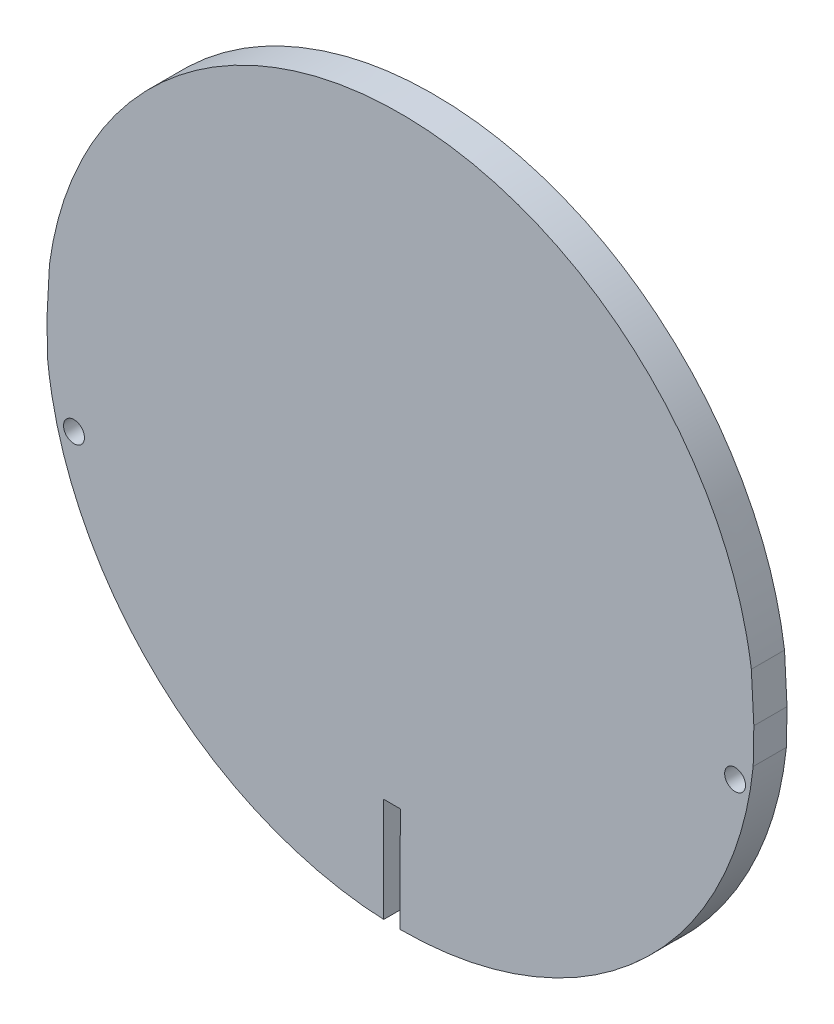
SolidWorks part; units mm, degrees
ref_plane "Front Plane" through (0, 0, 0) normal (0, 0, 1) x (1, 0, 0)
ref_plane "Top Plane" through (0, 0, 0) normal (0, 1, 0) x (1, 0, 0)
ref_plane "Right Plane" through (0, 0, 0) normal (1, 0, 0) x (0, 0, -1)
sketch "Sketch1" plane through (0, 0, 377.2094) normal (0, 0, 1) x (1, 0, 0)
  line L8 (-33.7995, -0.0171) -> (-33.7401, -3.4188)
  line L9 (33.7402, -3.4188) -> (33.7996, -0.0171)
  line L10 (33.7996, -0.0171) -> (33.5604, 4.5461)
  line L11 (-33.5604, 4.5461) -> (-33.7995, -0.0171)
  line L12 (-33.7995, -0.0171) -> (-33.7401, -3.4188)
  line L13 (33.7402, -3.4188) -> (33.7996, -0.0171)
  line L14 (33.7996, -0.0171) -> (33.5604, 4.5461)
  line L15 (-33.5604, 4.5461) -> (-33.7995, -0.0171)
  spline S4 degree 3 poles (3584.2823, 1682.1592) (1891.8794, 981.7265) (-94.167, 198.9267) (-32.2457, -10.4865) (-31.7386, -11.9486) (-31.1278, -13.3816) (-30.6974, -14.3304) (-30.4704, -14.8019) (-29.2902, -17.1196) (-27.6449, -19.7403) (-25.6469, -22.1139) (-24.5884, -23.2589) (-24.2247, -23.6345) (-23.482, -24.3673) (-21.5901, -26.1504) (-18.7057, -28.3179) (-15.9808, -29.8236) (-14.107, -30.7477) (-13.1527, -31.1642) (-10.2562, -32.2793) (-7.778, -32.9883) (-5.2143, -33.4059) (-4.182, -33.5493) (-3.6613, -33.6093) (-2.1045, -33.752) (-1.0692, -33.7985) (2.0296, -33.8017) (4.086, -33.6221) (7.1551, -33.0587) (8.1781, -32.8207) (10.177, -32.2566) (11.1581, -31.9299) (14.0494, -30.8232) (15.9079, -29.9178) (18.1367, -28.5564) (18.5769, -28.2731) (19.4387, -27.6895) (20.707, -26.7866) (21.9036, -25.8034) (23.4386, -24.4244) (24.5444, -23.3394) (25.5786, -22.174) (26.2518, -21.3787) (26.581, -20.9708) (28.1709, -18.9029) (29.2697, -17.1529) (30.6789, -14.3959) (31.1088, -13.4548) (31.8841, -11.5261) (32.23, -10.5349) (99.7864, 216.9461) (-2290.3338, 992.2204) (3927.4834, -154.8641) knots -6.532325 -6.532325 -6.532325 -6.532325 0.0625 0.0625 0.09375 0.109375 0.109375 0.125 0.125 0.1875 0.21875 0.21875 0.234375 0.234375 0.25 0.3125 0.34375 0.34375 0.375 0.375 0.4375 0.453125 0.453125 0.46875 0.46875 0.5 0.5 0.5625 0.5625 0.59375 0.59375 0.625 0.625 0.6875 0.6875 0.703125 0.703125 0.71875 0.75 0.75 0.78125 0.796875 0.796875 0.8125 0.8125 0.875 0.875 0.90625 0.90625 0.9375 0.9375 8.025461 8.025461 8.025461 8.025461 only from (-33.7401, -3.4188) to (33.7402, -3.4188)
  spline S5 degree 3 poles (-3548.6792, -1753.5382) (-1588.5004, -923.6815) (94.7973, -181.1863) (31.8946, 11.4023) (31.3611, 12.8157) (30.7295, 14.1982) (30.2866, 15.113) (30.0537, 15.5679) (28.8457, 17.8053) (27.7362, 19.4878) (25.8529, 21.8475) (25.1886, 22.6067) (23.7865, 24.0699) (23.0451, 24.7766) (20.7523, 26.7783) (18.3111, 28.5582) (15.6406, 29.9959) (14.2667, 30.657) (13.8011, 30.8682) (12.8648, 31.268) (12.3937, 31.4568) (10.0246, 32.3475) (7.1153, 33.1595) (4.1023, 33.5707) (2.0702, 33.754) (1.0537, 33.7991) (-1.9787, 33.8028) (-4.4872, 33.5877) (-6.9715, 33.0844) (-7.9632, 32.8597) (-8.4594, 32.7353) (-9.9337, 32.3298) (-10.8974, 32.0168) (-13.7346, 30.9575) (-15.5548, 30.0922) (-17.7347, 28.7982) (-18.1659, 28.5288) (-19.0186, 27.9683) (-19.4392, 27.6779) (-20.674, 26.7832) (-21.4652, 26.1531) (-23.7487, 24.1676) (-25.1511, 22.7176) (-26.7425, 20.7348) (-27.0534, 20.3287) (-27.655, 19.5045) (-28.5257, 18.252) (-29.3043, 16.9523) (-30.7455, 14.2933) (-31.5513, 12.4411) (-32.5069, 9.533) (-32.7811, 8.5477) (-77.2289, -184.7715) (1567.6211, -755.0924) (-3962.2208, 280.2012) knots -6.201583 -6.201583 -6.201583 -6.201583 0.0625 0.0625 0.09375 0.109375 0.109375 0.125 0.125 0.1875 0.1875 0.21875 0.21875 0.25 0.25 0.3125 0.34375 0.34375 0.359375 0.359375 0.375 0.375 0.4375 0.46875 0.46875 0.5 0.5 0.5625 0.578125 0.578125 0.59375 0.59375 0.625 0.625 0.6875 0.6875 0.703125 0.703125 0.71875 0.71875 0.75 0.75 0.8125 0.8125 0.828125 0.828125 0.84375 0.875 0.875 0.9375 0.9375 0.96875 0.96875 7.021867 7.021867 7.021867 7.021867 only from (33.5604, 4.5461) to (-33.5604, 4.5461)
  spline S6 degree 3 poles (-33.7401, -3.4188) (-33.5219, -5.4967) (-33.1218, -7.5236) (-32.2457, -10.4865) (-31.7386, -11.9486) (-31.1278, -13.3816) (-30.6974, -14.3304) (-30.4704, -14.8019) (-29.2902, -17.1196) (-27.6449, -19.7403) (-25.6469, -22.1139) (-24.5884, -23.2589) (-24.2247, -23.6345) (-23.482, -24.3673) (-21.5901, -26.1504) (-18.7057, -28.3179) (-15.9808, -29.8236) (-14.107, -30.7477) (-13.1527, -31.1642) (-10.2562, -32.2793) (-7.778, -32.9883) (-5.2143, -33.4059) (-4.182, -33.5493) (-3.6613, -33.6093) (-2.1045, -33.752) (-1.0692, -33.7985) (2.0296, -33.8017) (4.086, -33.6221) (7.1551, -33.0587) (8.1781, -32.8207) (10.177, -32.2566) (11.1581, -31.9299) (14.0494, -30.8232) (15.9079, -29.9178) (18.1367, -28.5564) (18.5769, -28.2731) (19.4387, -27.6895) (20.707, -26.7866) (21.9036, -25.8034) (23.4386, -24.4244) (24.5444, -23.3394) (25.5786, -22.174) (26.2518, -21.3787) (26.581, -20.9708) (28.1709, -18.9029) (29.2697, -17.1529) (30.6789, -14.3959) (31.1088, -13.4548) (31.8841, -11.5261) (32.23, -10.5349) (33.1196, -7.5393) (33.5217, -5.4996) (33.7402, -3.4188) knots 0 0 0 0 0.0625 0.0625 0.09375 0.109375 0.109375 0.125 0.125 0.1875 0.21875 0.21875 0.234375 0.234375 0.25 0.3125 0.34375 0.34375 0.375 0.375 0.4375 0.453125 0.453125 0.46875 0.46875 0.5 0.5 0.5625 0.5625 0.59375 0.59375 0.625 0.625 0.6875 0.6875 0.703125 0.703125 0.71875 0.75 0.75 0.78125 0.796875 0.796875 0.8125 0.8125 0.875 0.875 0.90625 0.90625 0.9375 0.9375 1 1 1 1
  spline S7 degree 3 poles (33.5604, 4.5461) (33.2821, 6.5674) (32.8314, 8.5342) (31.8946, 11.4023) (31.3611, 12.8157) (30.7295, 14.1982) (30.2866, 15.113) (30.0537, 15.5679) (28.8457, 17.8053) (27.7362, 19.4878) (25.8529, 21.8475) (25.1886, 22.6067) (23.7865, 24.0699) (23.0451, 24.7766) (20.7523, 26.7783) (18.3111, 28.5582) (15.6406, 29.9959) (14.2667, 30.657) (13.8011, 30.8682) (12.8648, 31.268) (12.3937, 31.4568) (10.0246, 32.3475) (7.1153, 33.1595) (4.1023, 33.5707) (2.0702, 33.754) (1.0537, 33.7991) (-1.9787, 33.8028) (-4.4872, 33.5877) (-6.9715, 33.0844) (-7.9632, 32.8597) (-8.4594, 32.7353) (-9.9337, 32.3298) (-10.8974, 32.0168) (-13.7346, 30.9575) (-15.5548, 30.0922) (-17.7347, 28.7982) (-18.1659, 28.5288) (-19.0186, 27.9683) (-19.4392, 27.6779) (-20.674, 26.7832) (-21.4652, 26.1531) (-23.7487, 24.1676) (-25.1511, 22.7176) (-26.7425, 20.7348) (-27.0534, 20.3287) (-27.655, 19.5045) (-28.5257, 18.252) (-29.3043, 16.9523) (-30.7455, 14.2933) (-31.5513, 12.4411) (-32.5069, 9.533) (-32.7811, 8.5477) (-33.2376, 6.5619) (-33.4209, 5.5589) (-33.5604, 4.5461) knots 0 0 0 0 0.0625 0.0625 0.09375 0.109375 0.109375 0.125 0.125 0.1875 0.1875 0.21875 0.21875 0.25 0.25 0.3125 0.34375 0.34375 0.359375 0.359375 0.375 0.375 0.4375 0.46875 0.46875 0.5 0.5 0.5625 0.578125 0.578125 0.59375 0.59375 0.625 0.625 0.6875 0.6875 0.703125 0.703125 0.71875 0.71875 0.75 0.75 0.8125 0.8125 0.828125 0.828125 0.84375 0.875 0.875 0.9375 0.9375 0.96875 0.96875 1 1 1 1
  dimension "D1" = 1
extrude "Boss-Extrude1" add sketch "Sketch1" against normal blind 3.175
sketch "Sketch2" plane through (0, 0, 377.2094) normal (0, 0, 1) x (1, 0, 0)
  circle A0 centre (32.0093, -5.359) radius 1 construction
  circle A1 centre (-31.2161, -8.1644) radius 1 construction
  circle A2 centre (32.0093, -5.359) radius 1
  circle A3 centre (-31.2161, -8.1644) radius 1
extrude "Cut-Extrude1" cut sketch "Sketch2" against normal blind 3.175
sketch "Sketch3" plane through (0, 0, 377.2094) normal (0, 0, 1) x (1, 0, 0)
  line L0 (0, 0) -> (-0.0186, -33.7996) construction
  line L1 (-1.6006, -23.7996) -> (1.5744, -23.7996)
  line L13 (-1.6006, -23.7996) -> (-1.6006, -34.7702)
  line L14 (-1.6006, -34.7702) -> (1.5744, -34.7702)
  line L15 (1.5744, -34.7702) -> (1.5744, -23.7996)
  line L16 (-23.7238, -25.4681) -> (-15.8908, -17.7871)
  line L17 (-18.1137, -15.5202) -> (-15.8908, -17.7871)
  line L18 (-18.1137, -15.5202) -> (-25.9468, -23.2011)
  line L19 (-25.9468, -23.2011) -> (-23.7238, -25.4681)
  line L20 (25.6995, -23.473) -> (17.9421, -15.7156)
  line L21 (15.697, -17.9607) -> (17.9421, -15.7156)
  line L22 (15.697, -17.9607) -> (23.4544, -25.718)
  line L23 (23.4544, -25.718) -> (25.6995, -23.473)
  spline S0 degree 3 poles (-33.7401, -3.4188) (-33.5219, -5.4967) (-33.1218, -7.5236) (-32.2457, -10.4865) (-31.7386, -11.9486) (-31.1278, -13.3816) (-30.6974, -14.3304) (-30.4704, -14.8019) (-29.2902, -17.1196) (-27.6449, -19.7403) (-25.6469, -22.1139) (-24.5884, -23.2589) (-24.2247, -23.6345) (-23.482, -24.3673) (-21.5901, -26.1504) (-18.7057, -28.3179) (-15.9808, -29.8236) (-14.107, -30.7477) (-13.1527, -31.1642) (-10.2562, -32.2793) (-7.778, -32.9883) (-5.2143, -33.4059) (-4.182, -33.5493) (-3.6613, -33.6093) (-2.1045, -33.752) (-1.0692, -33.7985) (2.0296, -33.8017) (4.086, -33.6221) (7.1551, -33.0587) (8.1781, -32.8207) (10.177, -32.2566) (11.1581, -31.9299) (14.0494, -30.8232) (15.9079, -29.9178) (18.1367, -28.5564) (18.5769, -28.2731) (19.4387, -27.6895) (20.707, -26.7866) (21.9036, -25.8034) (23.4386, -24.4244) (24.5444, -23.3394) (25.5786, -22.174) (26.2518, -21.3787) (26.581, -20.9708) (28.1709, -18.9029) (29.2697, -17.1529) (30.6789, -14.3959) (31.1088, -13.4548) (31.8841, -11.5261) (32.23, -10.5349) (33.1196, -7.5393) (33.5217, -5.4996) (33.7402, -3.4188) knots 0 0 0 0 0.0625 0.0625 0.09375 0.109375 0.109375 0.125 0.125 0.1875 0.21875 0.21875 0.234375 0.234375 0.25 0.3125 0.34375 0.34375 0.375 0.375 0.4375 0.453125 0.453125 0.46875 0.46875 0.5 0.5 0.5625 0.5625 0.59375 0.59375 0.625 0.625 0.6875 0.6875 0.703125 0.703125 0.71875 0.75 0.75 0.78125 0.796875 0.796875 0.8125 0.8125 0.875 0.875 0.90625 0.90625 0.9375 0.9375 1 1 1 1 construction
  spline S1 degree 3 poles (-29.7439, -3.1693) (-29.5425, -4.9938) (-29.1806, -6.7723) (-28.3985, -9.3718) (-27.9469, -10.6542) (-27.4049, -11.9108) (-27.0234, -12.7428) (-26.8223, -13.1562) (-25.777, -15.1877) (-24.8075, -16.7189) (-23.1487, -18.8713) (-22.5611, -19.5643) (-21.3169, -20.9015) (-20.6591, -21.5463) (-18.624, -23.3704) (-17.1738, -24.4556) (-14.8518, -25.8775) (-14.053, -26.3166) (-12.4057, -27.1253) (-11.5665, -27.4902) (-9.0202, -28.4663) (-7.2783, -28.9639) (-5.0414, -29.3813) (-4.591, -29.4543) (-3.6842, -29.5798) (-3.2268, -29.6322) (-1.8585, -29.7573) (-0.9486, -29.7984) (1.7745, -29.802) (3.5812, -29.6462) (6.2772, -29.154) (7.1764, -28.9453) (8.9343, -28.4515) (9.7972, -28.1659) (12.3402, -27.1984) (13.975, -26.407) (15.935, -25.2158) (16.3227, -24.9673) (17.0818, -24.4557) (17.4541, -24.1919) (18.5504, -23.3772) (19.2536, -22.8033) (20.6067, -21.5958) (21.2566, -20.9622) (22.1897, -19.9653) (22.4938, -19.6252) (23.0876, -18.929) (23.378, -18.5719) (24.7831, -16.7576) (25.7554, -15.2227) (27.0047, -12.8053) (27.3857, -11.9801) (28.0744, -10.2893) (28.3827, -9.42) (29.1782, -6.7888) (29.5422, -4.9973) (29.7439, -3.1693) knots 0 0 0 0 0.0625 0.0625 0.09375 0.109375 0.109375 0.125 0.125 0.1875 0.1875 0.21875 0.21875 0.25 0.25 0.3125 0.3125 0.34375 0.34375 0.375 0.375 0.4375 0.4375 0.453125 0.453125 0.46875 0.46875 0.5 0.5 0.5625 0.5625 0.59375 0.59375 0.625 0.625 0.6875 0.6875 0.703125 0.703125 0.71875 0.71875 0.75 0.75 0.78125 0.78125 0.796875 0.796875 0.8125 0.8125 0.875 0.875 0.90625 0.90625 0.9375 0.9375 1 1 1 1 construction
  point P10 (-0.0131, -23.7996)
  point P18 (0, 0)
  point P19 (0, 0)
  point P24 (0, 0)
  point P26 (0, 0)
  dimension "D1" = 3.175
  dimension "D2" = 10
  dimension "D3" = 2
  dimension "D4" = 2
extrude "Cut-Extrude2" cut sketch "Sketch3" against normal up to surface (3.175 mm away)
